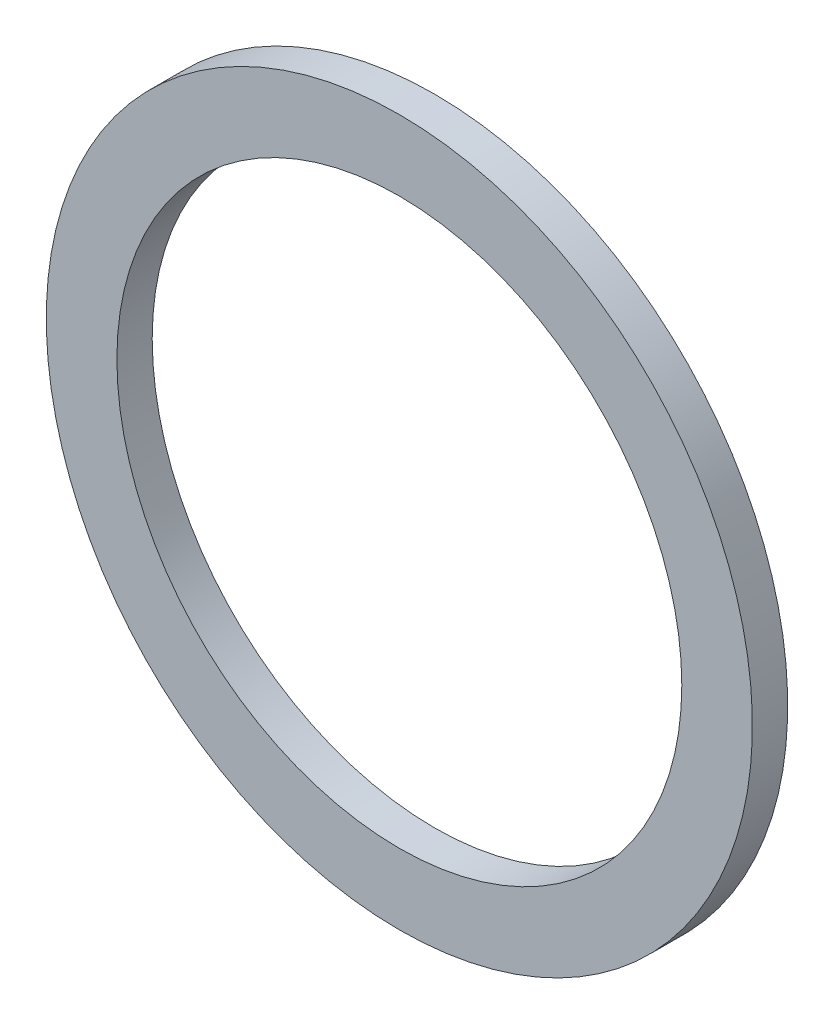
SolidWorks part; units mm, degrees
material "SUS304H"
ref_plane "Front Plane" through (0, 0, 0) normal (0, 0, 1) x (1, 0, 0)
ref_plane "Top Plane" through (0, 0, 0) normal (0, 1, 0) x (1, 0, 0)
ref_plane "Right Plane" through (0, 0, 0) normal (1, 0, 0) x (0, 0, -1)
sketch "Sketch1" plane through (0, 0, 0) normal (1, 0, 0) x (0, 0, -1)
  line L0 (0, 0) -> (-0.5, 0) construction
  line L2 (0, 0) -> (-0.5, 0)
  line L3 (0, 0) -> (0, 5)
  line L4 (0, 5) -> (-0.5, 5)
  line L5 (-0.5, 0) -> (-0.5, 5)
  dimension "T" = 0.5
  dimension "D" = 10
revolve "Revolve1" add sketch "Sketch1" angle 360 about L0
sketch "Sketch2" plane through (0, 0, 0) normal (1, 0, 0) x (0, 0, -1)
  line L0 (0, 0) -> (-0.5, 0) construction
  line L2 (0, 0) -> (-0.5, 0) construction
  line L3 (0, 0) -> (0, 4)
  line L4 (0, 4) -> (-0.5, 4)
  line L5 (-0.5, 0) -> (-0.5, 4)
  line L6 (-0.5, 5) -> (-0.5, -5) construction
  line L7 (0, 0) -> (-0.5, 0)
  dimension "D_s" = 8
revolve "Cut-Revolve1" cut sketch "Sketch2" angle 360 about L0
sketch "Sketch3" [suppressed] plane through (0, 0, 0) normal (1, 0, 0) x (0, 0, -1)
  line L0 (0, 0) -> (-0.1, 0) construction
  line L1 (0, -7.5) -> (0, 7.5) construction
  line L2 (-0.1, 4) -> (0, 4)
  line L5 (-0.1, 7.5) -> (-0.1, -7.5) construction
  line L7 (-0.1, -4) -> (0, -4) construction
  dimension "V" = 8
surface "Surface-Revolve1" [suppressed] sketch "Sketch3" parameters "D1"=360
other "SurfaceCut1" [suppressed]
sketch "Sketch4" [suppressed] plane through (0, 0, 0) normal (0, 0, 1) x (1, 0, 0)
  line L0 (0, 7.5) -> (0, 0) construction
  line L1 (-1.5, 6) -> (1.5, 6)
  line L2 (-1.5, 6) -> (-1.5, 0)
  line L3 (-1.5, 0) -> (1.5, 0)
  line L4 (1.5, 6) -> (1.5, 0)
  circle A0 centre (0, 0) radius 4 construction
  circle A1 centre (0, 0) radius 7.5 construction
  dimension "B_s" = 3
  dimension "T_s" = 2
extrude "Cut-Extrude1" [suppressed] cut sketch "Sketch4" along normal through all
